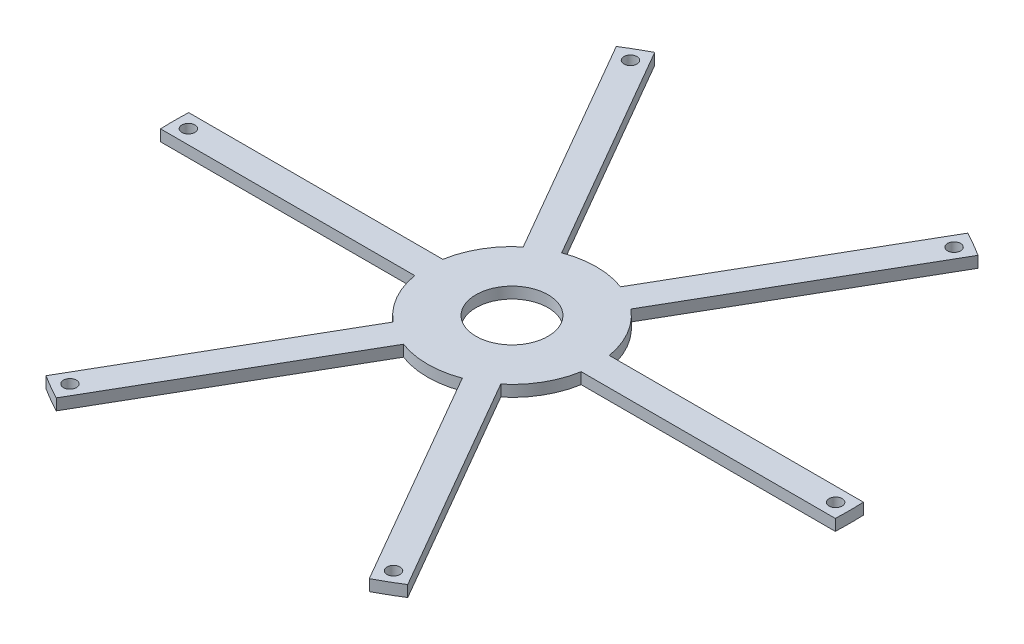
SolidWorks part; units mm, degrees
ref_plane "Front Plane" through (0, 0, 0) normal (0, 0, 1) x (1, 0, 0)
ref_plane "Top Plane" through (0, 0, 0) normal (0, 1, 0) x (1, 0, 0)
ref_plane "Right Plane" through (0, 0, 0) normal (1, 0, 0) x (0, 0, -1)
sketch "Sketch1" plane through (0, 0, 0) normal (0, 1, 0) x (1, 0, 0)
  line L0 (0, 0) -> (76.1338, 0) construction
  line L1 (18.7836, 3.175) -> (76.1338, 3.175)
  line L3 (18.7836, -3.175) -> (76.1338, -3.175)
  line L4 (76.1338, 3.175) -> (76.1338, -3.175) construction
  line L5 (12.1414, -14.6795) -> (40.8165, -64.3463)
  line L7 (6.6421, -17.8545) -> (35.3173, -67.5213)
  line L8 (40.8165, -64.3463) -> (35.3173, -67.5213) construction
  line L9 (-6.6421, -17.8545) -> (-35.3173, -67.5213)
  line L11 (-12.1414, -14.6795) -> (-40.8165, -64.3463)
  line L12 (-35.3173, -67.5213) -> (-40.8165, -64.3463) construction
  line L13 (-18.7836, -3.175) -> (-76.1338, -3.175)
  line L15 (-18.7836, 3.175) -> (-76.1338, 3.175)
  line L16 (-76.1338, -3.175) -> (-76.1338, 3.175) construction
  line L17 (-12.1414, 14.6795) -> (-40.8165, 64.3463)
  line L19 (-6.6421, 17.8545) -> (-35.3173, 67.5213)
  line L20 (-40.8165, 64.3463) -> (-35.3173, 67.5213) construction
  line L21 (6.6421, 17.8545) -> (35.3173, 67.5213)
  line L23 (12.1414, 14.6795) -> (40.8165, 64.3463)
  line L24 (35.3173, 67.5213) -> (40.8165, 64.3463) construction
  arc A0 (40.8165, 64.3463) -> (35.3173, 67.5213) centre (0, 0) ccw
  arc A1 (-12.1414, 14.6795) -> (-18.7836, 3.175) centre (0, 0) ccw
  arc A2 (6.6421, 17.8545) -> (-6.6421, 17.8545) centre (0, 0) ccw
  arc A3 (-18.7836, -3.175) -> (-12.1414, -14.6795) centre (0, 0) ccw
  arc A4 (-6.6421, -17.8545) -> (6.6421, -17.8545) centre (0, 0) ccw
  arc A5 (12.1414, -14.6795) -> (18.7836, -3.175) centre (0, 0) ccw
  arc A6 (18.7836, 3.175) -> (12.1414, 14.6795) centre (0, 0) ccw
  arc A7 (-35.3173, 67.5213) -> (-40.8165, 64.3463) centre (0, 0) ccw
  arc A8 (-76.1338, 3.175) -> (-76.1338, -3.175) centre (0, 0) ccw
  arc A9 (-40.8165, -64.3463) -> (-35.3173, -67.5213) centre (0, 0) ccw
  arc A10 (35.3173, -67.5213) -> (40.8165, -64.3463) centre (0, 0) ccw
  arc A11 (76.1338, -3.175) -> (76.1338, 3.175) centre (0, 0) ccw
  point P31 (0, 0)
  dimension "D1" = 152.4
  dimension "D2" = 38.1
  dimension "D3" = 6.35
  dimension "D4" = 6
extrude "Boss-Extrude1" add sketch "Sketch1" along normal blind 2.54
hole_wizard "5/8 Clearance Hole1" positions "Sketch3" profile "Sketch2" hole size "5/8" standard "ANSI Inch"
sketch "Sketch3" plane through (0, 2.54, 0) normal (0, 1, 0) x (1, 0, 0)
  point P0 (0, 0)
sketch "Sketch2" plane through (0, 2.54, 0) normal (1, 0, 0) x (0, 0, 1)
  line L0 (0, 0) -> (0, 43.2424)
  line L1 (0, 43.2424) -> (8.1356, 38.354)
  line L2 (8.1356, 38.354) -> (8.1356, 0)
  line L5 (8.1356, 0) -> (0, 0)
  line L10 (0, 43.2424) -> (-8.1356, 38.354) construction
  line L11 (0, -6.35) -> (0, 107.95) construction
  dimension "Hole Dia." = 16.2712
  dimension "Hole Depth" = 38.354
  dimension "Drill Angle" = 118
hole_wizard "#4 Clearance Hole1" positions "Sketch6" profile "Sketch4" hole size "#4" standard "ANSI Inch"
sketch "Sketch6" plane through (0, 2.54, 0) normal (0, 1, 0) x (1, 0, 0)
  line L0 (-76.2, 0) -> (-52.9675, 0) construction
  line L2 (0, 0) -> (-73.025, 0) construction
  arc A0 (-76.1338, 3.175) -> (-76.1338, -3.175) centre (0, 0) ccw construction
  point P0 (-73.025, 0)
  point P16 (-36.5125, 63.2415)
  point P17 (36.5125, 63.2415)
  point P18 (73.025, 0)
  point P19 (36.5125, -63.2415)
  point P20 (-36.5125, -63.2415)
  dimension "D1" = 73.025
  dimension "D3" = 73.025
  dimension "D2" = 6
sketch "Sketch4" plane through (-73.025, 2.54, 0) normal (1, 0, 0) x (0, 0, 1)
  line L0 (0, 0) -> (0, 39.2392)
  line L1 (0, 39.2392) -> (1.4732, 38.354)
  line L2 (1.4732, 38.354) -> (1.4732, 0)
  line L5 (1.4732, 0) -> (0, 0)
  line L10 (0, 39.2392) -> (-1.4732, 38.354) construction
  line L11 (0, -6.35) -> (0, 107.95) construction
  dimension "Hole Dia." = 2.9464
  dimension "Hole Depth" = 38.354
  dimension "Drill Angle" = 118
